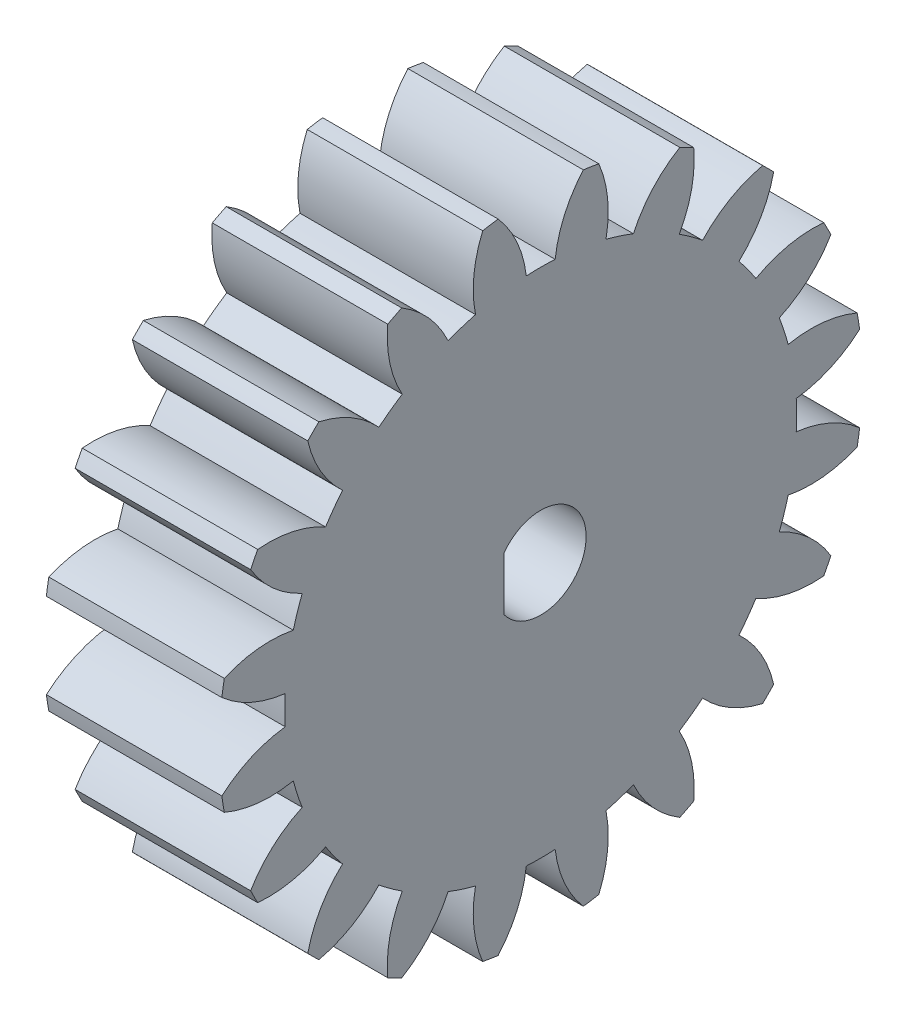
SolidWorks part; units mm, degrees
ref_plane "Plane1" through (0, 0, 0) normal (0, 0, 1) x (1, 0, 0)
ref_plane "Plane2" through (0, 0, 0) normal (0, 1, 0) x (1, 0, 0)
ref_plane "Plane3" through (0, 0, 0) normal (1, 0, 0) x (0, 0, -1)
other "Configuration Table"
sketch "HoldingSke" plane through (0, 0, 0) normal (0, 1, 0) x (1, 0, 0)
  line L0 (0, 0) -> (0.4698, -0.171)
  line L1 (-15, 0) -> (100, 0) construction
  line L2 (0, 0) -> (-2.1039, 2.3779)
  line L3 (0, 0) -> (-11.863, 4.5341)
  line L4 (0, 0) -> (8.1152, 2.9537)
  line L5 (0, 0) -> (-46.8476, -17.4728)
  line L6 (0, 0) -> (-9.9476, -6.7116)
  line L7 (-2.1039, 2.3779) -> (8.6586, 51.2059)
  line L8 (-76.2, 54.61) -> (-76.1, 54.61)
  line L9 (-71.009, 38.7566) -> (-53.1078, 45.2721)
  line L10 (-76.2, 71.12) -> (104.1128, 71.12)
  line L11 (0, 0) -> (-12, 0)
  line L12 (-76.2, 101.6) -> (-76.133, 101.6)
  line L13 (24.9733, 27.94) -> (52.9518, 28.4284)
  line L14 (24.9733, 27.94) -> (24.9743, 27.94)
  line L15 (24.9733, 27.94) -> (100.4006, 29.5858)
  line L16 (-63.627, -2) -> (-12.827, -2)
  circle A0 centre (0, 0) radius 0.4
  circle A1 centre (0, 0) radius 17.499
  circle A2 centre (0, 0) radius 37.5
  circle A3 centre (0, 0) radius 0.4
  dimension "MHD" = 34.998
  dimension "Hub_dia" = 75
  dimension "Bore" = 0.8
  dimension "MBD" = 0.8
  dimension "Num_teeth" = 20
  dimension "Pitch" = 0.5
  dimension "Overall_len" = 50
  dimension "Show_teeth" = 20
  dimension "Thickness" = 12
  dimension "OAL" = 50.0001
  dimension "T_dim" = 0.1
  dimension "Ap" = 20
  dimension "H" = 19.05
  dimension "Pitch_radius" = 180.3128
  dimension "Width" = 12
  dimension "Backlash" = 0.067
  dimension "Addendum_fac" = 1
  dimension "Dedendum_fac" = 1.25
  dimension "Clearance_fac" = 0.25
  dimension "Dedendum_add" = 0.001
  dimension "Module" = 2
sketch "BasProSke" plane through (0, 0, 0) normal (0, 1, 0) x (1, 0, 0)
  line L0 (-10, 0) -> (60, 0) construction
  line L1 (0, 0) -> (0, 22)
  line L2 (0, 0) -> (12, 0)
  line L3 (12, 0) -> (12, 22)
  line L4 (12, 22) -> (0, 22)
  dimension "Thickness" = 12
  dimension "Diameter" = 44
revolve "Base-Revolve" add sketch "BasProSke" angle 360 about L0
sketch "TooCutSke" plane through (0, 0, 0) normal (1, 0, 0) x (0, 0, -1)
  line L1 (0, 0) -> (0, 107) construction
  line L2 (0, 0) -> (-1.6864, 19.9288) construction
  line L3 (0, 0) -> (-6.2409, 39.4033) construction
  line L4 (-1.6864, 19.9288) -> (-3.1204, 19.7016) construction
  arc A0 (0.9862, 17.4712) -> (-0.9862, 17.4712) centre (0, 0) ccw
  arc A1 (2.9329, 21.8293) -> (-2.9329, 21.8293) centre (0, 0) ccw
  circle A2 centre (0, 0) radius 20 construction
  circle A3 centre (0, 0) radius 18.7939 construction
  arc A4 (-0.9862, 17.4712) -> (-2.9329, 21.8293) centre (-8.9313, 16.536) ccw
  arc A5 (2.9329, 21.8293) -> (0.9862, 17.4712) centre (8.9313, 16.536) ccw
  dimension "Root_dia" = 34.998
  dimension "Overcut_dia" = 44.0508
  dimension "Pitch_dia" = 40
  dimension "Base_dia" = 37.5877
  dimension "Flank_rad" = 8
  dimension "Half_ang" = 9
  dimension "Half_CT" = 1.4519
extrude "ToothCut" cut sketch "TooCutSke" along normal through all
fillet "Breaks" [suppressed] radius 0.04
fillet "RootFillets" [suppressed] radius 0.501
pattern_circular "TeethCuts" count 20 every 18 about axis through (-10, 0, 0) along (1, 0, 0) of "ToothCut", "RootFillets", "Breaks"
sketch "HubNeaOneSke" plane through (0, 0, 0) normal (-1, 0, 0) x (0, 0, 1)
  circle A0 centre (0, 0) radius 17.499
  dimension "Diameter" = 34.998
extrude "HubNearOne" [suppressed] add sketch "HubNeaOneSke" along normal blind 38.0001
sketch "HubNeaBotSke" plane through (0, 0, 0) normal (-1, 0, 0) x (0, 0, 1)
  circle A0 centre (0, 0) radius 17.499
  dimension "Diameter" = 34.998
extrude "HubNearBoth" [suppressed] add sketch "HubNeaBotSke" along normal blind 19
ref_plane "FarPln" through (12, 0, 0) normal (1, 0, 0) x (0, 0, -1)
sketch "HubFarSke" plane through (12, 0, 0) normal (1, 0, 0) x (0, 0, -1)
  circle A0 centre (0, 0) radius 17.499
  dimension "Diameter" = 34.998
extrude "HubFar" [suppressed] add sketch "HubFarSke" along normal blind 19
sketch "BorSke" plane through (0, 0, 0) normal (1, 0, 0) x (0, 0, -1)
  circle A0 centre (0, 0) radius 0.4
  dimension "Diameter" = 0.8
extrude "Bore" cut sketch "BorSke" along normal mid plane 100.0001
sketch "KeySke" plane through (0, 0, 0) normal (1, 0, 0) x (0, 0, -1)
  line L0 (-0.05, 0) -> (-0.05, 0.5)
  line L1 (-0.05, 0.5) -> (0.05, 0.5)
  line L2 (0.05, 0.5) -> (0.05, 0)
  line L3 (0, 0) -> (0, 34) construction
  line L4 (-0.05, 0) -> (0.05, 0)
  dimension "Offset" = 0.5
  dimension "Width" = 0.1
extrude "Keyway" [suppressed] cut sketch "KeySke" along normal mid plane 100.0001
pattern_circular "Keyway2" [suppressed] count 2 every 90 about axis through (-10, 0, 0) along (1, 0, 0)
sketch "Çizim1" plane through (12, 0, 0) normal (1, 0, 0) x (0, 0, -1)
  line L0 (-2.5265, 1.805) -> (-2.5265, -1.805)
  circle A0 centre (0, 0) radius 3.105
  dimension "D1" = 6.21
  dimension "D2" = 3.61
extrude "Kes-Ekstrüzyon1" cut sketch "Çizim1" against normal blind 100 contours L0 A0
equation "' \"Module@HoldingSke\" = 6.35"
equation "' \"Num_teeth@HoldingSke\" = 12"
equation "' \"Ap@HoldingSke\" =  20"
equation "' \"Ap@HoldingSke\" = 20"
equation "' \"Width@HoldingSke\" = 0.5 * 25.4"
equation "' \"Hub_dia@HoldingSke\"= 1 * 25.4"
equation "' \"Hub_dia@HoldingSke\" = 1 * 25.4"
equation "' \"Overall_len@HoldingSke\" = 1.0 * 25.4"
equation "' \"Bore@HoldingSke\" = 0.75 * 25.4"
equation "' \"T_dim@HoldingSke\" = 0.1 * 25.4"
equation "' \"Width@KeySke\" = 0.25 * 25.4"
equation "' \"Show_teeth@HoldingSke\" = 13"
equation "' \"Backlash@HoldingSke\" = 0.009 * 25.4"
equation "' \"Addendum_fac@HoldingSke\" = 1.0"
equation "' \"Dedendum_fac@HoldingSke\" = 1.25"
equation "' \"Dedendum_add@HoldingSke\" = 0.00005 * 25.4"
equation "' \"Clearance_fac@HoldingSke\" = 0.25"
equation "\"Pitch@HoldingSke\" = 1 / \"Module@HoldingSke\""
equation "\"Overcut_dia@TooCutSke\" = (\"Num_teeth@HoldingSke\" + 2 * \"Addendum_fac@HoldingSke\") / \"Pitch@HoldingSke\" + 0.002 * 25.4"
equation "\"Pitch_dia@TooCutSke\" = \"Num_teeth@HoldingSke\" / \"Pitch@HoldingSke\""
equation "\"Base_dia@TooCutSke\" = \"Num_teeth@HoldingSke\" / \"Pitch@HoldingSke\" * cos((\"Ap@HoldingSke\"  * 3.14159265 / 180))"
equation "\"Root_dia@TooCutSke\" = (\"Num_teeth@HoldingSke\" + 2) / \"Pitch@HoldingSke\" - 2 * (\"Addendum_fac@HoldingSke\" + \"Dedendum_fac@HoldingSke\") / \"Pitch@HoldingSke\" - \"Dedendum_add@HoldingSke\" * 2"
equation "\"Half_ang@TooCutSke\" = 180 / \"Num_teeth@HoldingSke\""
equation "\"Half_CT@TooCutSke\" = \"Num_teeth@HoldingSke\" / \"Pitch@HoldingSke\" * sin((3.14159265 / 2 / \"Num_teeth@HoldingSke\")) / 2 - 7 * \"Backlash@HoldingSke\" / 4"
equation "\"Flank_rad@TooCutSke\" = \"Num_teeth@HoldingSke\" / \"Pitch@HoldingSke\" / 5"
equation "\"Radius@RootFillets\" = \"Clearance_fac@HoldingSke\" / \"Pitch@HoldingSke\" + \"Dedendum_add@HoldingSke\""
equation "\"Break_rad@Breaks\" = 0.02 / \"Pitch@HoldingSke\""
equation "\"Thickness@HoldingSke\" = \"Width@HoldingSke\""
equation "\"OAL@HoldingSke\" = \"Thickness@HoldingSke\""
equation "\"MHD@HoldingSke\" = (\"Num_teeth@HoldingSke\" + 2) / \"Pitch@HoldingSke\" - 2 * (\"Addendum_fac@HoldingSke\" + \"Dedendum_fac@HoldingSke\")  / \"Pitch@HoldingSke\" - \"Dedendum_add@HoldingSke\" * 2"
equation "\"MBD@HoldingSke\" = (\"Num_teeth@HoldingSke\" + 2) / \"Pitch@HoldingSke\" - 2 * (\"Addendum_fac@HoldingSke\" + \"Dedendum_fac@HoldingSke\")  / \"Pitch@HoldingSke\" - \"Dedendum_add@HoldingSke\" * 2 - 0.002 * 25.4"
equation "\"MHD@HoldingSke\" = ((sgn( \"MHD@HoldingSke\" - \"Hub_dia@HoldingSke\" )-1)*( \"MHD@HoldingSke\" - \"Hub_dia@HoldingSke\" ))/-2+ \"Hub_dia@HoldingSke\""
equation "\"MBD@HoldingSke\" = ((sgn( \"MBD@HoldingSke\" - \"Bore@HoldingSke\" )-1)*( \"MBD@HoldingSke\" - \"Bore@HoldingSke\" ))/-2+ \"Bore@HoldingSke\""
equation "\"OAL@HoldingSke\" = ((sgn( \"OAL@HoldingSke\" - \"Overall_len@HoldingSke\" )+1)*( \"OAL@HoldingSke\" - \"Overall_len@HoldingSke\" ))/2 + \"Overall_len@HoldingSke\" + 0.000002 * 25.4"
equation "\"Num_teeth@TeethCuts\" = int( \"Show_teeth@HoldingSke\" ) + 1"
equation "\"Num_teeth@TeethCuts\" = ((sgn( \"Num_teeth@TeethCuts\" - \"Num_teeth@HoldingSke\" )-1)*( \"Num_teeth@TeethCuts\" - \"Num_teeth@HoldingSke\" ))/-2+ \"Num_teeth@HoldingSke\""
equation "\"Num_teeth@TeethCuts\" = ((sgn( \"Num_teeth@TeethCuts\" - 2.0)+1)*( \"Num_teeth@TeethCuts\" - 2.0))/2 +2.0"
equation "\"Angle@TeethCuts\" = 360.0 / \"Num_teeth@HoldingSke\""
equation "\"Diameter@BasProSke\" = (\"Num_teeth@HoldingSke\" + 2 * \"Addendum_fac@HoldingSke\") / \"Pitch@HoldingSke\""
equation "\"Thickness@BasProSke\"  = \"Thickness@HoldingSke\""
equation "' \"Fillet_rad@BasProSke\" =  \"Thickness@HoldingSke\" * 0.05"
equation "' \"Fillet_rad@BasProSke\" = \"Thickness@HoldingSke\" * 0.05"
equation "\"MHD@HoldingSke\" = ((sgn( \"MHD@HoldingSke\" - \"Root_dia@TooCutSke\" )-1)*( \"MHD@HoldingSke\" - \"Root_dia@TooCutSke\" ))/-2+ \"Root_dia@TooCutSke\""
equation "\"Diameter@HubNeaOneSke\" = \"MHD@HoldingSke\""
equation "\"Length@HubNearOne\" = \"OAL@HoldingSke\" - \"Thickness@BasProSke\""
equation "\"Diameter@HubNeaBotSke\" = \"MHD@HoldingSke\""
equation "\"Length@HubNearBoth\" = ( \"OAL@HoldingSke\" - \"Thickness@BasProSke\" ) / 2.0"
equation "\"Thickness@FarPln\" = \"Thickness@BasProSke\""
equation "\"Diameter@HubFarSke\" = \"MHD@HoldingSke\""
equation "\"Length@HubFar\" = ( \"OAL@HoldingSke\" - \"Thickness@BasProSke\" ) / 2.0"
equation "\"Diameter@BorSke\" = \"MBD@HoldingSke\""
equation "\"D1@Bore\" = \"OAL@HoldingSke\" * 2.0"
equation "\"D1@Keyway\" = \"OAL@HoldingSke\" * 2.0"
equation "\"Offset@KeySke\" = \"T_dim@HoldingSke\" + \"MBD@HoldingSke\" / 2.0"
